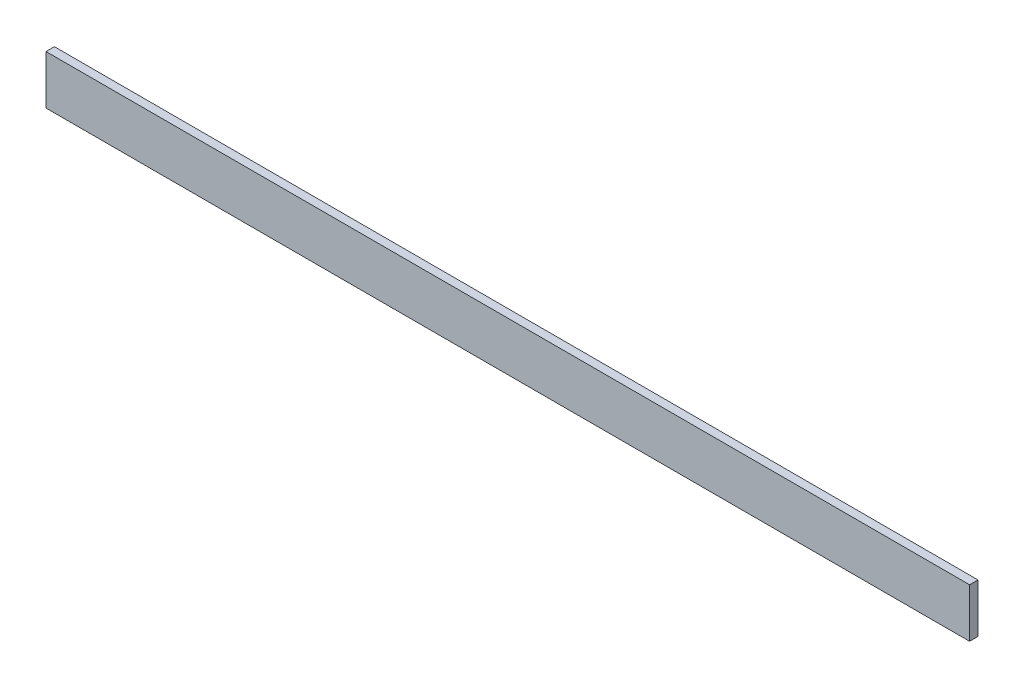
SolidWorks part; units mm, degrees
material "Acrylic (Medium-high impact)"
ref_plane "Front Plane" through (0, 0, 0) normal (0, 0, 1) x (1, 0, 0)
ref_plane "Top Plane" through (0, 0, 0) normal (0, 1, 0) x (1, 0, 0)
ref_plane "Right Plane" through (0, 0, 0) normal (1, 0, 0) x (0, 0, -1)
sketch "Sketch1" plane through (0, 0, 0) normal (0, 0, 1) x (1, 0, 0)
  line L1 (-99.5041, 9.1736) -> (560.4959, 9.1736)
  line L2 (-99.5041, 9.1736) -> (-99.5041, -25.8264)
  line L3 (-99.5041, -25.8264) -> (560.4959, -25.8264)
  line L4 (560.4959, 9.1736) -> (560.4959, -25.8264)
  dimension "D1" = 35
  dimension "D2" = 660
extrude "Boss-Extrude1" add sketch "Sketch1" along normal blind 6
